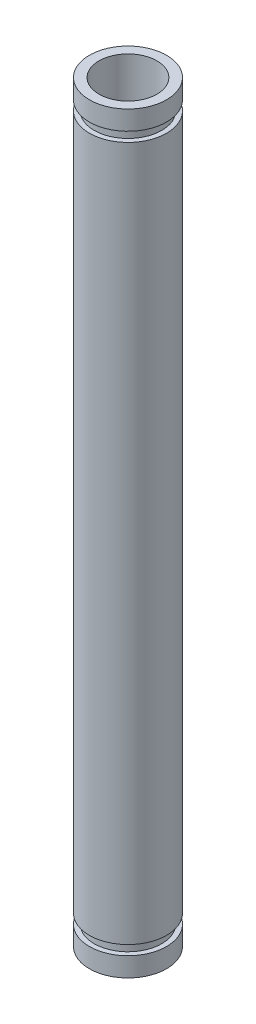
SolidWorks part; units mm, degrees
material "1060 Alloy"
ref_plane "Front Plane" through (0, 0, 0) normal (0, 0, 1) x (1, 0, 0)
ref_plane "Top Plane" through (0, 0, 0) normal (0, 1, 0) x (1, 0, 0)
ref_plane "Right Plane" through (0, 0, 0) normal (1, 0, 0) x (0, 0, -1)
sketch "Sketch1" plane through (0, 0, 0) normal (0, 0, 1) x (1, 0, 0)
  line L0 (0, 43.9529) -> (0, -24.464) construction
  line L1 (-3, 39) -> (-4, 39)
  line L2 (-4, 39) -> (-4, 37)
  line L3 (-4, 37) -> (-3.5, 37)
  line L4 (-3.5, 37) -> (-3.5, 36)
  line L5 (-3.5, 36) -> (-4, 36)
  line L6 (-4, 36) -> (-4, -36)
  line L7 (-7.2845, 0) -> (7.1842, 0) construction
  line L8 (-3, 39) -> (-3, -39)
  line L9 (-3, -39) -> (-4, -39)
  line L10 (-3.5, -36) -> (-4, -36)
  line L11 (-3.5, -37) -> (-3.5, -36)
  line L12 (-4, -37) -> (-3.5, -37)
  line L13 (-4, -39) -> (-4, -37)
  point P16 (-3, 0)
  point P17 (-4, 0)
  dimension "D1" = 1
  dimension "D2" = 2
  dimension "D3" = 1
  dimension "D4" = 8
  dimension "D5" = 72
  dimension "D6" = 0.5
revolve "Revolve1" add sketch "Sketch1" angle 360 about L0
